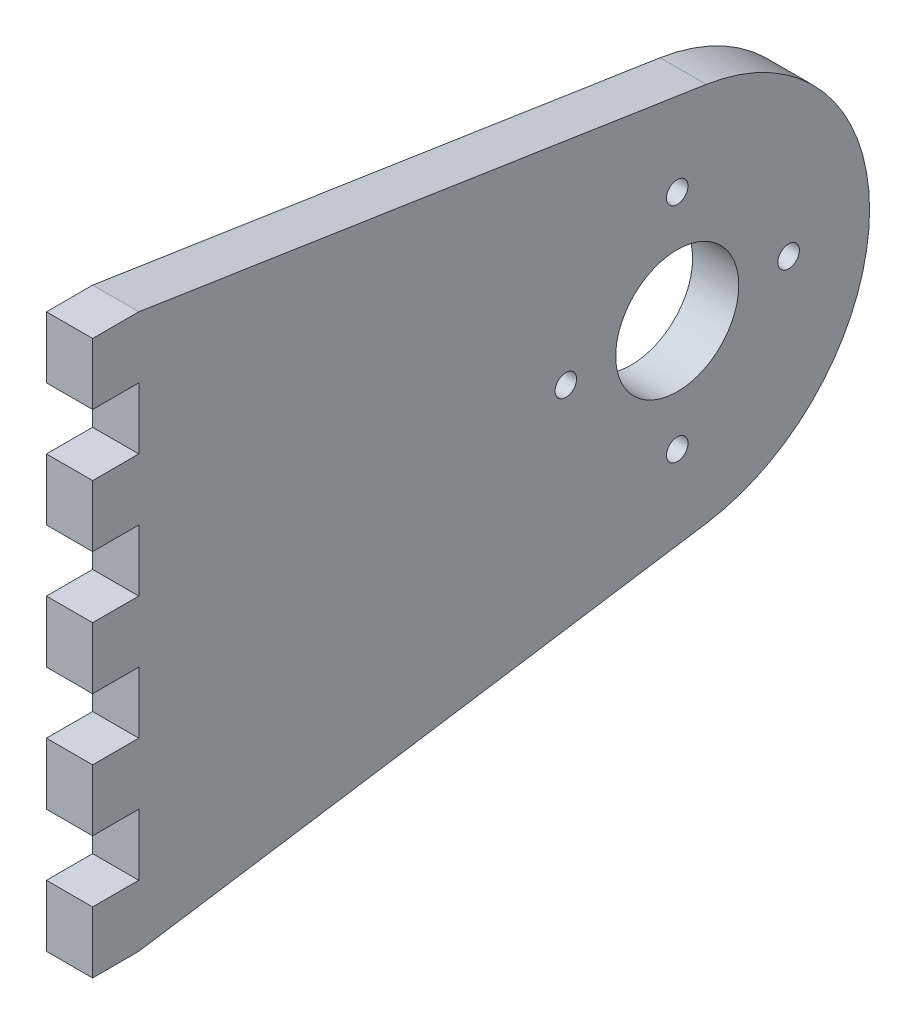
SolidWorks part; units mm, degrees
ref_plane "Front Plane" through (0, 0, 0) normal (0, 0, 1) x (1, 0, 0)
ref_plane "Top Plane" through (0, 0, 0) normal (0, 1, 0) x (1, 0, 0)
ref_plane "Right Plane" through (0, 0, 0) normal (1, 0, 0) x (0, 0, -1)
sketch "Sketch1" plane through (0, 0, 0) normal (1, 0, 0) x (0, 0, -1)
  line L0 (-38, 18) -> (-35, 18)
  line L1 (-38, 18) -> (-38, 14)
  line L2 (-38, -18) -> (-35, -18)
  line L3 (-38, 14) -> (-35, 14)
  line L4 (-35, 14) -> (-35, 10)
  line L5 (-35, 10) -> (-38, 10)
  line L6 (-38, 6) -> (-35, 6)
  line L7 (-35, 6) -> (-35, 2)
  line L8 (-35, 2) -> (-38, 2)
  line L9 (-38, -14) -> (-35, -14)
  line L10 (-35, -14) -> (-35, -10)
  line L11 (-35, -10) -> (-38, -10)
  line L12 (-38, -6) -> (-35, -6)
  line L13 (-35, -6) -> (-35, -2)
  line L14 (-35, -2) -> (-38, -2)
  line L15 (-38, 10) -> (-38, 6)
  line L16 (-38, 2) -> (-38, -2)
  line L17 (-38, -6) -> (-38, -10)
  line L18 (-38, -14) -> (-38, -18)
  line L19 (-35, 18) -> (1.8904, 12.3562)
  line L20 (-35, -18) -> (1.8904, -12.3562)
  circle A0 centre (0, 0) radius 4
  circle A1 centre (-7.24, 0) radius 0.7
  circle A2 centre (0, 7.24) radius 0.7
  circle A3 centre (7.24, 0) radius 0.7
  circle A4 centre (0, -7.24) radius 0.7
  arc A5 (1.8904, -12.3562) -> (1.8904, 12.3562) centre (0, 0) ccw
  point P14 (-38, 0)
  point P18 (0, 0)
  dimension "D1" = 8
  dimension "D2" = 1.4
  dimension "D5" = 4
  dimension "D9" = 25
  dimension "D3" = 7.24
  dimension "D6" = 35
  dimension "D7" = 4
  dimension "D8" = 3
  dimension "D4" = 4
extrude "Boss-Extrude1" add sketch "Sketch1" along normal blind 3
